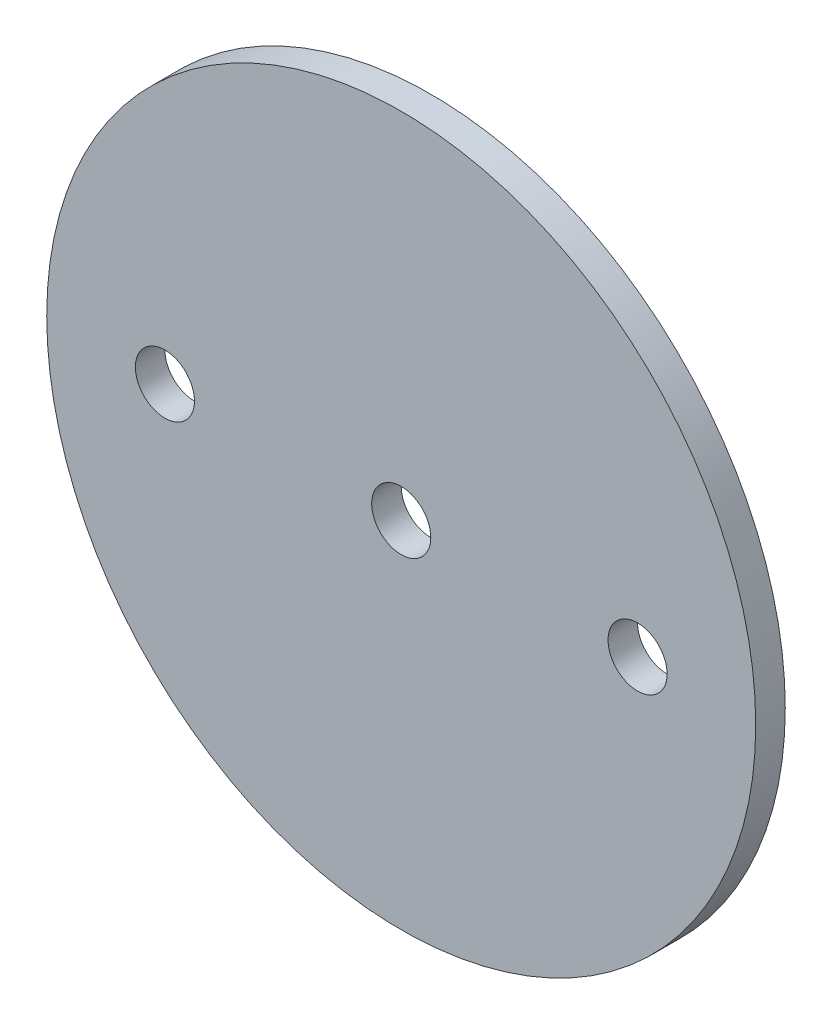
SolidWorks part; units mm, degrees
ref_plane "Front Plane" through (0, 0, 0) normal (0, 0, 1) x (1, 0, 0)
ref_plane "Top Plane" through (0, 0, 0) normal (0, 1, 0) x (1, 0, 0)
ref_plane "Right Plane" through (0, 0, 0) normal (1, 0, 0) x (0, 0, -1)
sketch "Sketch1" plane through (0, 0, 0) normal (0, 0, 1) x (1, 0, 0)
  circle A0 centre (0, 0) radius 38.1
  dimension "D1" = 76.2
extrude "Boss-Extrude1" add sketch "Sketch1" along normal mid plane 3.175
sketch "Sketch2" plane through (0, 0, 1.5875) normal (0, 0, 1) x (1, 0, 0)
  line L0 (-1000, 0) -> (49000, 0) construction
  point P1 (0, 0)
  point P4 (25.4, 0)
  point P5 (-25.4, 0)
  dimension "D1" = 25.4
  dimension "D2" = 50.8
hole_wizard "1/4 (0.25) Diameter Hole1" positions "Sketch2" profile "Sketch3" hole size "1/4" standard "ANSI Inch" end condition through all
sketch "Sketch3" plane through (-25.4, 0, 1.5875) normal (1, 0, 0) x (0, -1, 0)
  line L0 (0, 0) -> (0, 3.175)
  line L1 (0, 3.175) -> (3.175, 3.175)
  line L2 (3.175, 3.175) -> (3.175, 0)
  line L5 (3.175, 0) -> (0, 0)
  line L11 (0, -6.35) -> (0, 107.95) construction
  dimension "Thru Hole Dia." = 6.35
  dimension "Thru Hole Depth" = 3.175
equation "\"AIRFRAME_OD\"= 3.091in"
equation "\"AIRFRAME_ID\"= 3.00in"
equation "\"FLAT_T\" = 0.125in"
equation "\"NOSE_EXP_L\"= 3.5in"
equation "\"NOSE_SHOULDER_L\" = 5in"
equation "\"MAIN_L\" = 30in"
equation "\"RECO_COUP_L\" = 6in"
equation "\"RECO_SWITCH_L\" = 1.5in"
equation "\"DROGUE_L\" = 14in"
equation "\"ATS_FORE_COUP_L\" = 4in"
equation "\"ATS_AFT_COUP_L\" = 4in"
equation "\"LOWER_L\" = 16in"
equation "\"FIN_N\" = 4"
equation "\"CR_AFT_X\" = 0.5in"
equation "\"CR_FORE_X\" = 6in"
equation "\"FIN_ROOT\" = 5in"
equation "\"FIN_X\" = 0.75in"
equation "\"MOTOR_OD\" = 2.25in"
equation "\"MOTOR_ID\" = 2.126in"
equation "\"COUPLER_OD\" = 2.998in"
equation "\"COUPLER_ID\" = 2.875in"
equation "\"D1@Sketch1\"=\"AIRFRAME_ID\""
equation "\"D1@Boss-Extrude1\"=\"FLAT_T\""
equation "\"RECO_ROD_X\" = 1.5in"
equation "\"ATS_ROD_X\" = 2in"
equation "\"D1@Sketch2\"=\"ATS_ROD_X\"*0.5"
equation "\"D2@Sketch2\"=\"ATS_ROD_X\""
